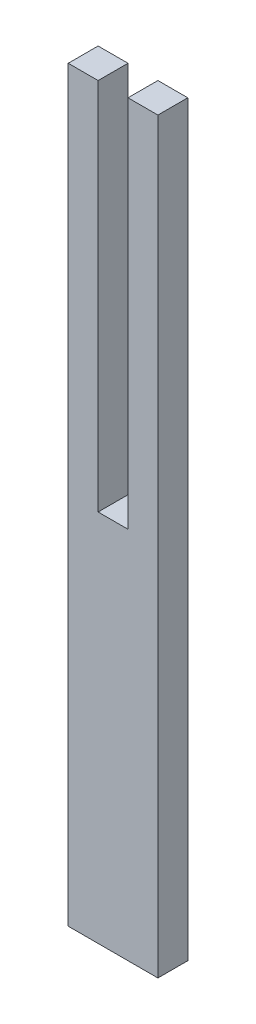
SolidWorks part; units mm, degrees
ref_plane "Front Plane" through (0, 0, 0) normal (0, 0, 1) x (1, 0, 0)
ref_plane "Top Plane" through (0, 0, 0) normal (0, 1, 0) x (1, 0, 0)
ref_plane "Right Plane" through (0, 0, 0) normal (1, 0, 0) x (0, 0, -1)
sketch "Sketch1" plane through (0, 0, 0) normal (0, 0, 1) x (1, 0, 0)
  line L0 (-28.2847, 42.8961) -> (-28.2847, -84.1039)
  line L1 (-28.2847, -84.1039) -> (-13.0447, -84.1039)
  line L2 (-13.0447, -84.1039) -> (-13.0447, 42.8961)
  line L3 (-13.0447, 42.8961) -> (-18.1247, 42.8961)
  line L4 (-18.1247, 42.8961) -> (-18.1247, -20.6039)
  line L5 (-18.1247, -20.6039) -> (-23.2047, -20.6039)
  line L6 (-23.2047, -20.6039) -> (-23.2047, 42.8961)
  line L7 (-23.2047, 42.8961) -> (-28.2847, 42.8961)
  dimension "D1" = 15.24
  dimension "D2" = 5.08
  dimension "D3" = 5.08
  dimension "D4" = 127
  dimension "D5" = 127
  dimension "D6" = 63.5
extrude "Boss-Extrude1" add sketch "Sketch1" along normal blind 5.08
